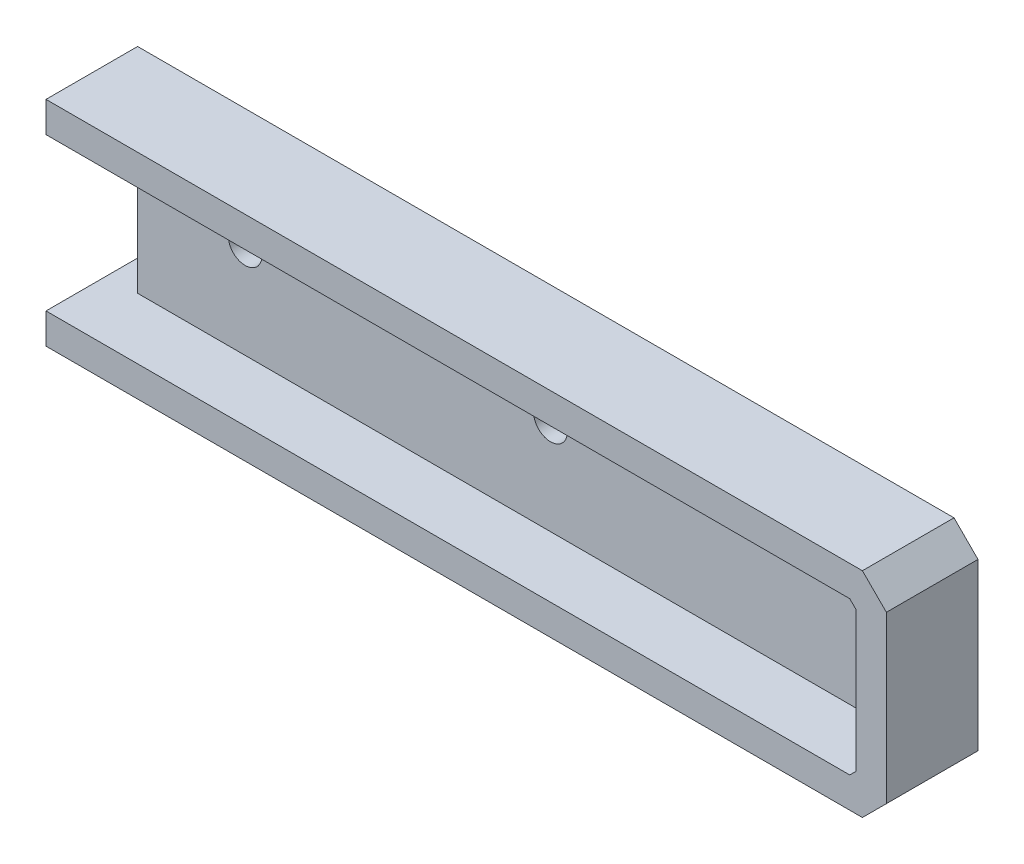
SolidWorks part; units mm, degrees
ref_plane "Front Plane" through (0, 0, 0) normal (0, 0, 1) x (1, 0, 0)
ref_plane "Top Plane" through (0, 0, 0) normal (0, 1, 0) x (1, 0, 0)
ref_plane "Right Plane" through (0, 0, 0) normal (1, 0, 0) x (0, 0, -1)
sketch "Sketch1" plane through (0, 0, 0) normal (0, 0, 1) x (1, 0, 0)
  line L0 (72.3909, 0) -> (72.3909, -25)
  line L17 (72.3909, 0) -> (195, 0)
  line L18 (199, 0) -> (195, 0)
  line L19 (199, 0) -> (200, -1)
  line L20 (200, -1) -> (200, -24)
  line L21 (199, -25) -> (200, -24)
  line L22 (195, -25) -> (199, -25)
  line L23 (195, -25) -> (72.3909, -25)
  circle A4 centre (90, -9.5) radius 2.75
  circle A5 centre (140, -9.5) radius 2.75
  point P31 (0, -9.5)
extrude "Boss-Extrude1" add sketch "Sketch1" along normal blind 5
sketch "Sketch2" plane through (0, 0, 0) normal (0, 0, -1) x (-1, 0, 0)
  line L12 (-72.3909, -25) -> (-72.3909, 0)
  line L13 (-72.3909, 0) -> (-199, 0)
  line L14 (-199, 0) -> (-200, -1)
  line L15 (-200, -1) -> (-200, -24)
  line L16 (-200, -24) -> (-199, -25)
  line L17 (-199, -25) -> (-72.3909, -25)
  line L19 (-72.3909, 0) -> (-199, 0)
  line L20 (-199, 0) -> (-200, -1)
  line L21 (-200, -1) -> (-200, -24)
  line L22 (-200, -24) -> (-199, -25)
  line L23 (-199, -25) -> (-72.3909, -25)
  line L24 (-72.3909, -25) -> (-67.3909, -25)
  line L25 (-72.3909, 0) -> (-67.3909, 0)
  line L26 (-67.3909, -30) -> (-67.3909, -25)
  line L30 (-67.3909, -30) -> (-67.3909, 5)
  line L31 (-67.3909, 5) -> (-201.0711, 5)
  line L32 (-201.0711, 5) -> (-205, 1.0711)
  line L33 (-205, 1.0711) -> (-205, -26.0711)
  line L34 (-205, -26.0711) -> (-201.0711, -30)
  line L35 (-201.0711, -30) -> (-67.3909, -30)
  line L36 (-67.3909, 0) -> (-67.3909, 5)
  line L37 (-67.3909, 5) -> (-201.0711, 5)
  line L38 (-201.0711, 5) -> (-205, 1.0711)
  line L39 (-205, 1.0711) -> (-205, -26.0711)
  line L40 (-205, -26.0711) -> (-201.0711, -30)
  line L41 (-201.0711, -30) -> (-67.3909, -30)
  dimension "D1" = 0
  dimension "D2" = 5
extrude "Boss-Extrude4" add sketch "Sketch2" against normal blind 15
